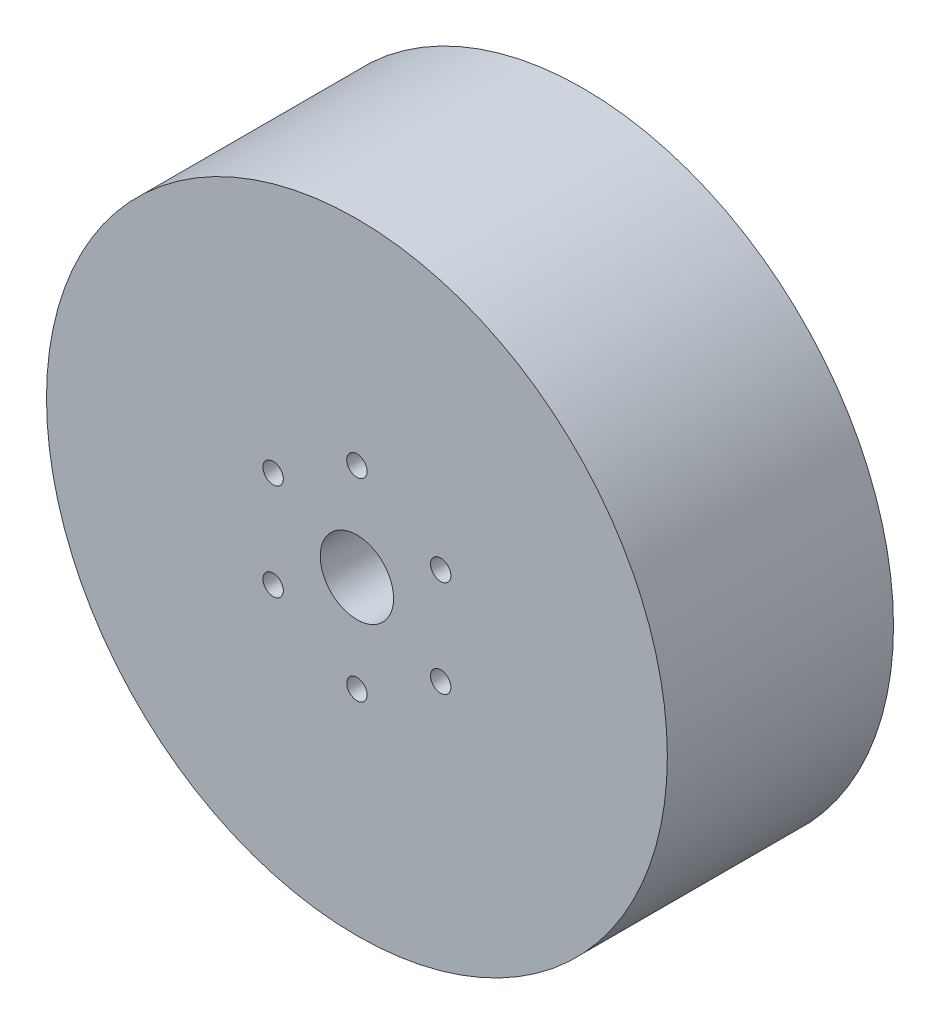
SolidWorks part; units mm, degrees
ref_plane "Front Plane" through (0, 0, 0) normal (0, 0, 1) x (1, 0, 0)
ref_plane "Top Plane" through (0, 0, 0) normal (0, 1, 0) x (1, 0, 0)
ref_plane "Right Plane" through (0, 0, 0) normal (1, 0, 0) x (0, 0, -1)
sketch "Sketch1" plane through (0, 0, 0) normal (0, 0, 1) x (1, 0, 0)
  circle A0 centre (0, 0) radius 76.2
  circle A1 centre (0, 0) radius 9
  circle A2 centre (0, 0) radius 23.75 construction
  circle A3 centre (0, 23.75) radius 2.5
  circle A4 centre (20.5686, 11.8759) radius 2.5
  circle A5 centre (20.5696, -11.8741) radius 2.5
  circle A6 centre (0.002, -23.75) radius 2.5
  circle A7 centre (-20.5666, -11.8759) radius 2.5
  circle A8 centre (-20.5676, 11.8741) radius 2.5
  dimension "D1" = 152.4
  dimension "D2" = 18
  dimension "D3" = 47.5
  dimension "D4" = 5
  dimension "D5" = 6
extrude "Boss-Extrude1" add sketch "Sketch1" along normal blind 55.52
